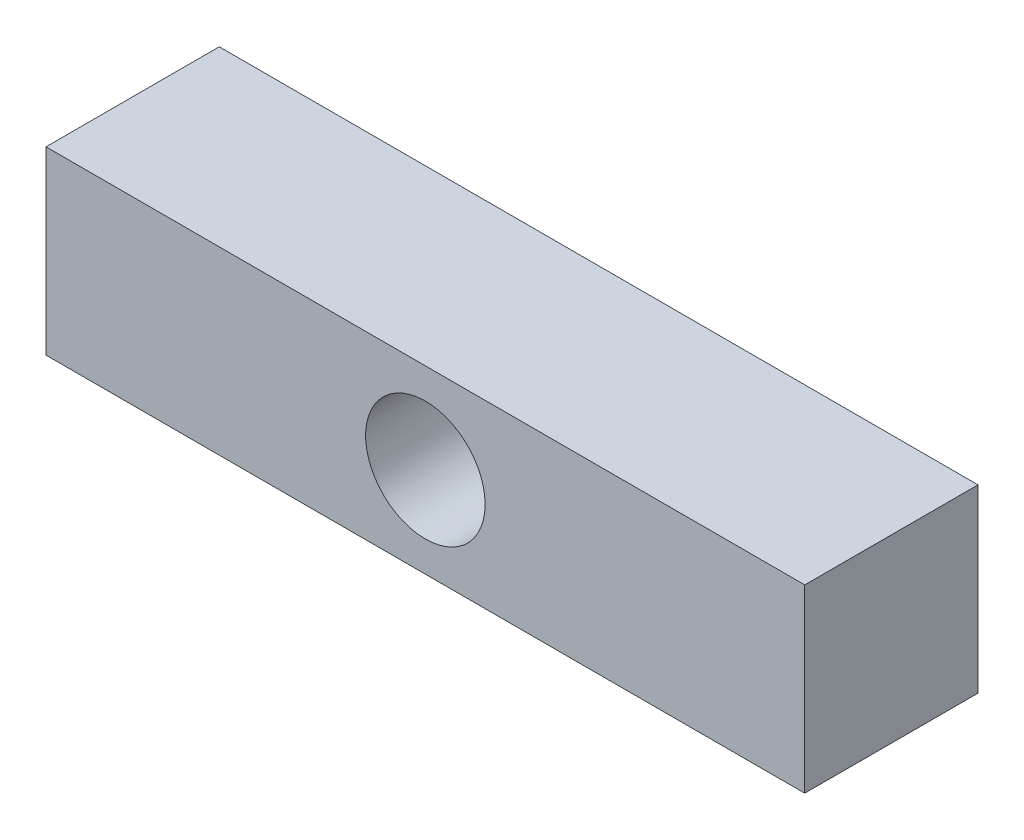
SolidWorks part; units mm, degrees
ref_plane "Front Plane" through (0, 0, 0) normal (0, 0, 1) x (1, 0, 0)
ref_plane "Top Plane" through (0, 0, 0) normal (0, 1, 0) x (1, 0, 0)
ref_plane "Right Plane" through (0, 0, 0) normal (1, 0, 0) x (0, 0, -1)
sketch "Sketch1" plane through (0, 0, 0) normal (0, 1, 0) x (1, 0, 0)
  line L1 (-12.7, -2.9) -> (12.7, -2.9)
  line L2 (-12.7, -2.9) -> (-12.7, 2.9)
  line L3 (-12.7, 2.9) -> (12.7, 2.9)
  line L4 (12.7, -2.9) -> (12.7, 2.9)
  line L5 (-12.7, -2.9) -> (12.7, 2.9) construction
  line L6 (-12.7, 2.9) -> (12.7, -2.9) construction
  point P0 (0, 0)
  dimension "D1" = 25.4
  dimension "D2" = 5.8
extrude "Boss-Extrude1" add sketch "Sketch1" along normal blind 6.04
sketch "Sketch2" plane through (0, 0, 2.9) normal (0, 0, 1) x (1, 0, 0)
  line L0 (0, 6.04) -> (0, 0) construction
  line L1 (-12.7, 6.04) -> (12.7, 6.04) construction
  line L2 (-12.7, 3.02) -> (12.7, 3.02) construction
  line L3 (-12.7, 6.04) -> (-12.7, 0) construction
  line L4 (12.7, 6.04) -> (12.7, 0) construction
  circle A0 centre (0, 3.02) radius 2
  dimension "D1" = 4
extrude "Cut-Extrude1" cut sketch "Sketch2" against normal through all contours A0
